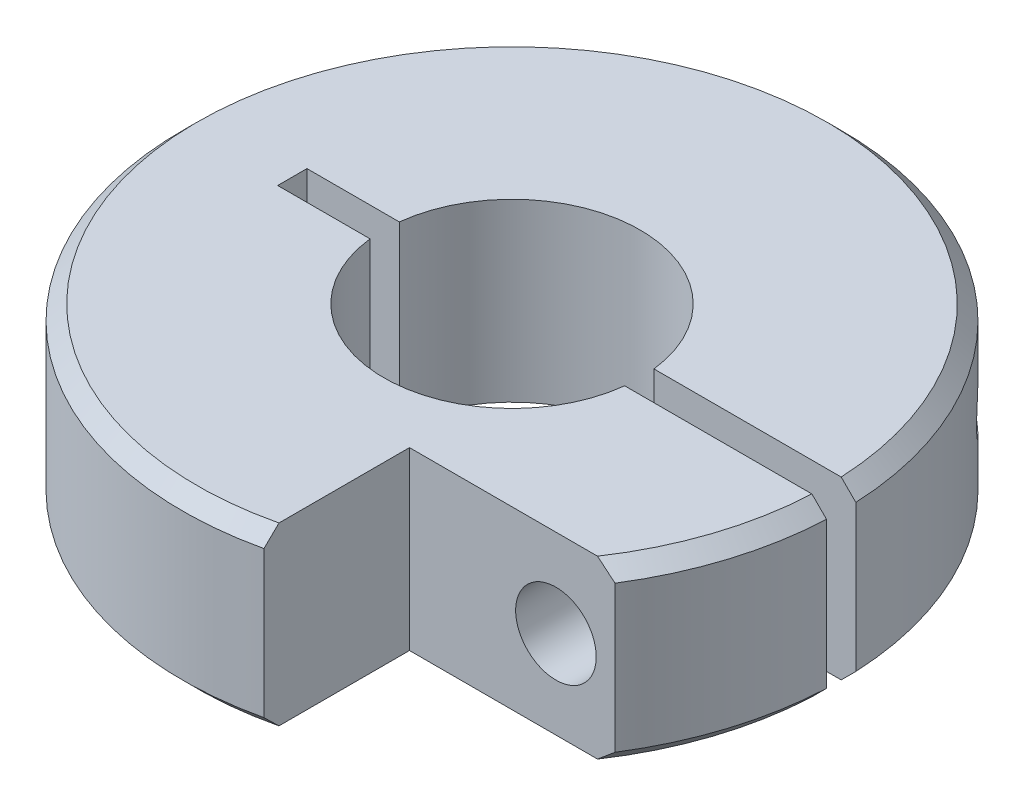
SolidWorks part; units mm, degrees
material "普通碳钢"
ref_plane "前视基准面" through (0, 0, 0) normal (0, 0, 1) x (1, 0, 0)
ref_plane "上视基准面" through (0, 0, 0) normal (0, 1, 0) x (1, 0, 0)
ref_plane "右视基准面" through (0, 0, 0) normal (1, 0, 0) x (0, 0, -1)
sketch "草图1" plane through (0, 0, 0) normal (0, 1, 0) x (1, 0, 0)
  circle A0 centre (0, 0) radius 22.5
  dimension "D2" = 45
extrude "凸台-拉伸1" add sketch "草图1" along normal mid plane 12
hole_wizard "M20 螺纹孔1" positions "草图13" profile "草图14" tap size "M20" standard "GB" end condition through all
sketch "草图13" plane through (0, 6, 0) normal (0, 1, 0) x (1, 0, 0)
  point P0 (0, 0)
sketch "草图14" plane through (0, 6, 0) normal (1, 0, 0) x (0, 0, 1)
  line L0 (0, 0) -> (0, 12)
  line L1 (0, 12) -> (8.75, 12)
  line L2 (8.75, 12) -> (8.75, 0)
  line L5 (8.75, 0) -> (0, 0)
  line L11 (0, -6.35) -> (0, 107.95) construction
  dimension "通孔螺纹孔钻头直径" = 17.5
  dimension "通孔螺纹孔钻头深度" = 12
cosmetic thread "孔螺蚊线3" parameters "D2"=20
sketch "草图2" plane through (0, 6, 0) normal (0, 1, 0) x (1, 0, 0)
  line L0 (-15, 0) -> (0, 0) construction
  line L1 (-15, 1) -> (22.5, 1)
  line L2 (-15, 1) -> (-15, -1)
  line L3 (-15, -1) -> (22.5, -1)
  line L4 (22.5, 1) -> (22.5, -1)
  circle A0 centre (0, 0) radius 22.5 construction
  dimension "D1" = 2
  dimension "D2" = 15
extrude "切除-拉伸1" cut sketch "草图2" against normal through all
sketch "草图6" plane through (0, 6, 0) normal (0, 1, 0) x (1, 0, 0)
  line L0 (19.0329, -12) -> (5, -12)
  line L1 (5, -12) -> (5, -21.9374)
  arc A0 (22.4778, 1) -> (22.4778, -1) centre (0, 0) ccw construction
  arc A1 (5, -21.9374) -> (19.0329, -12) centre (0, 0) ccw
  dimension "D1" = 5
  dimension "D2" = 12
extrude "切除-拉伸2" cut sketch "草图6" against normal through all
hole_wizard "Ø5.5 (5.5) 直径孔1" positions "草图8" profile "草图9" hole size "Ø5.5" standard "Iso"
sketch "草图8" plane through (0, 0, 12) normal (0, 0, 1) x (1, 0, 0)
  line L0 (15, 0) -> (19.0329, 0) construction
  line L1 (19.0329, -6) -> (19.0329, 6) construction
  point P0 (15, 0)
  dimension "D1" = 15
sketch "草图9" plane through (15, 0, 12) normal (1, 0, 0) x (0, -1, 0)
  line L0 (0, 0) -> (0, 11)
  line L1 (0, 11) -> (2.75, 11)
  line L2 (2.75, 11) -> (2.75, 0)
  line L5 (2.75, 0) -> (0, 0)
  line L11 (0, -6.35) -> (0, 107.95) construction
  dimension "通孔孔直径" = 5.5
  dimension "通孔孔深度" = 11
hole_wizard "M5 螺纹孔2" positions "草图11" profile "草图10" tap size "M5" standard "Gb" end condition through all
sketch "草图11" plane through (-28, -6, -1) normal (0, 0, 1) x (1, 0, 0)
  point P0 (43, 6)
sketch "草图10" plane through (15, 0, -1) normal (1, 0, 0) x (0, -1, 0)
  line L0 (0, 0) -> (0, 21.5)
  line L1 (0, 21.5) -> (2.1, 21.5)
  line L2 (2.1, 21.5) -> (2.1, 0)
  line L5 (2.1, 0) -> (0, 0)
  line L11 (0, -6.35) -> (0, 107.95) construction
  dimension "通孔螺纹孔钻头直径" = 4.2
  dimension "通孔螺纹孔钻头深度" = 21.5
cosmetic thread "孔螺蚊线2" parameters "D2"=5
chamfer "倒角1" distance 1 angle 45 4 edges at (-17.8966, -6, -13.6368) (21.4717, -6, 6.7243) (21.4717, 6, 6.7243) (-17.8966, 6, -13.6368)
